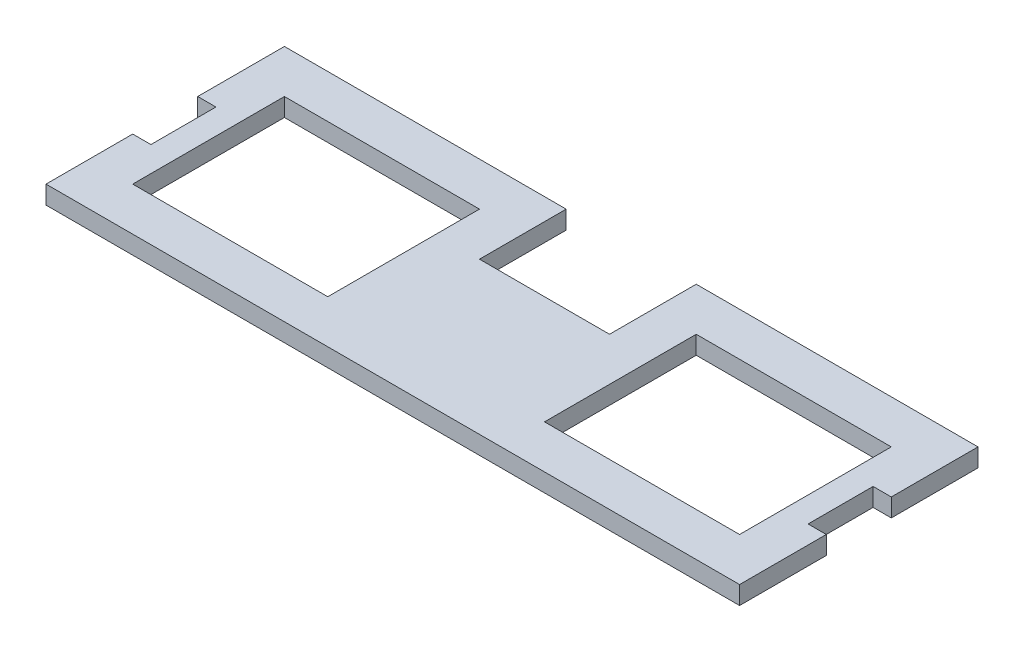
SolidWorks part; units mm, degrees
ref_plane "Front Plane" through (0, 0, 0) normal (0, 0, 1) x (1, 0, 0)
ref_plane "Top Plane" through (0, 0, 0) normal (0, 1, 0) x (1, 0, 0)
ref_plane "Right Plane" through (0, 0, 0) normal (1, 0, 0) x (0, 0, -1)
sketch "Sketch1" plane through (0, 0, 0) normal (0, 1, 0) x (1, 0, 0)
  line L1 (0, 0) -> (203.2, 0)
  line L2 (0, 0) -> (0, 69.85)
  line L3 (0, 69.85) -> (203.2, 69.85)
  line L4 (203.2, 0) -> (203.2, 69.85)
  dimension "D1" = 69.85
  dimension "D2" = 203.2
extrude "Base" add sketch "Sketch1" along normal blind 5.334
sketch "Sketch2" plane through (0, 5.334, 0) normal (0, 1, 0) x (1, 0, 0)
  line L0 (0, 69.85) -> (0, 0) construction
  line L1 (0, 44.45) -> (5.334, 44.45)
  line L2 (0, 44.45) -> (0, 25.4)
  line L3 (0, 25.4) -> (5.334, 25.4)
  line L4 (5.334, 44.45) -> (5.334, 25.4)
  line L5 (101.6, 69.85) -> (101.6, -49930.15) construction
  line L6 (0, 0) -> (203.2, 0) construction
  line L7 (203.2, 69.85) -> (0, 69.85) construction
  line L8 (197.866, 44.45) -> (197.866, 25.4)
  line L9 (203.2, 25.4) -> (197.866, 25.4)
  line L10 (203.2, 44.45) -> (203.2, 25.4)
  line L11 (203.2, 44.45) -> (197.866, 44.45)
  point P10 (101.6, 69.85)
  dimension "D2" = 19.05
  dimension "D3" = 25.4
  dimension "D4" = 5.334
extrude "Slots" cut sketch "Sketch2" against normal through all
sketch "Sketch3" plane through (0, 5.334, 0) normal (0, 1, 0) x (1, 0, 0)
  line L0 (203.2, 69.85) -> (0, 69.85) construction
  line L1 (82.55, 69.85) -> (120.65, 69.85)
  line L2 (82.55, 69.85) -> (82.55, 44.45)
  line L3 (82.55, 44.45) -> (120.65, 44.45)
  line L4 (120.65, 69.85) -> (120.65, 44.45)
  line L5 (82.55, 44.45) -> (0, 44.45) construction
  line L7 (0, 69.85) -> (0, 44.45) construction
  line L9 (120.65, 44.45) -> (203.2, 44.45) construction
  line L10 (203.2, 44.45) -> (203.2, 69.85) construction
  dimension "D1" = 38.1
  dimension "D2" = 25.4
extrude "Center Cutout" cut sketch "Sketch3" against normal through all
sketch "Sketch4" plane through (0, 5.334, 0) normal (0, 1, 0) x (1, 0, 0)
  line L0 (101.6, 0) -> (101.6, 50000) construction
  line L1 (0, 0) -> (203.2, 0) construction
  line L63 (69.85, 44.45) -> (69.85, 57.15)
  line L64 (69.85, 57.15) -> (12.7, 57.15)
  line L65 (12.7, 57.15) -> (12.7, 44.45)
  line L66 (69.85, 44.45) -> (69.85, 57.15)
  line L67 (69.85, 57.15) -> (12.7, 57.15)
  line L68 (12.7, 57.15) -> (12.7, 44.45)
  line L69 (69.85, 44.45) -> (69.85, 12.7)
  line L70 (12.7, 25.4) -> (12.7, 44.45)
  line L71 (12.7, 12.7) -> (203.2, 12.7)
  line L72 (12.7, 25.4) -> (12.7, 12.7)
  line L73 (12.7, 12.7) -> (69.85, 12.7)
  line L74 (12.7, 25.4) -> (12.7, 12.7)
  line L75 (190.5, 25.4) -> (190.5, 12.7)
  line L76 (190.5, 12.7) -> (133.35, 12.7)
  line L77 (190.5, 25.4) -> (190.5, 44.45)
  line L78 (133.35, 44.45) -> (133.35, 12.7)
  line L79 (190.5, 57.15) -> (190.5, 44.45)
  line L80 (133.35, 57.15) -> (190.5, 57.15)
  line L81 (133.35, 44.45) -> (133.35, 57.15)
  point P4 (101.6, 0)
  dimension "D1" = 12.7
  dimension "D2" = 12.7
extrude "Weight Reduction" cut sketch "Sketch4" against normal through all
equation "\"material\"= \"gmaterial@full.assembly\""
equation "\"D1@Base\"=\"material\""
equation "\"D4@Sketch2\"=\"material\""
